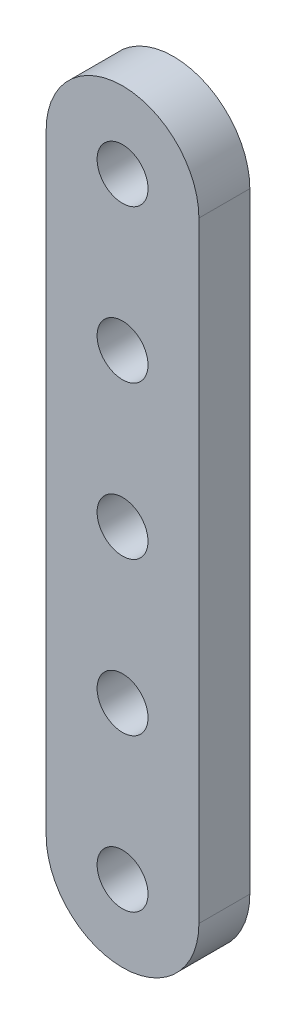
SolidWorks part; units mm, degrees
ref_plane "Alzado" through (0, 0, 0) normal (0, 0, 1) x (1, 0, 0)
ref_plane "Planta" through (0, 0, 0) normal (0, 1, 0) x (1, 0, 0)
ref_plane "Vista lateral" through (0, 0, 0) normal (1, 0, 0) x (0, 0, -1)
sketch "Model" plane through (0, 0, 0) normal (0, 0, 1) x (1, 0, 0)
  line L0 (213.2508, 152.4285) -> (213.2508, 188.4285)
  line L1 (204.2508, 188.4285) -> (204.2508, 152.4285)
  circle A0 centre (208.7508, 179.4285) radius 1.5
  circle A1 centre (208.7508, 188.4285) radius 1.5
  circle A2 centre (208.7508, 152.4285) radius 1.5
  circle A3 centre (208.7508, 161.4285) radius 1.5
  circle A4 centre (208.7508, 170.4285) radius 1.5
  arc A5 (204.2508, 152.4285) -> (213.2508, 152.4285) centre (208.7508, 152.4285) ccw
  arc A6 (213.2508, 188.4285) -> (204.2508, 188.4285) centre (208.7508, 188.4285) ccw
extrude "Saliente-Extruir1" add sketch "Model" along normal blind 3
